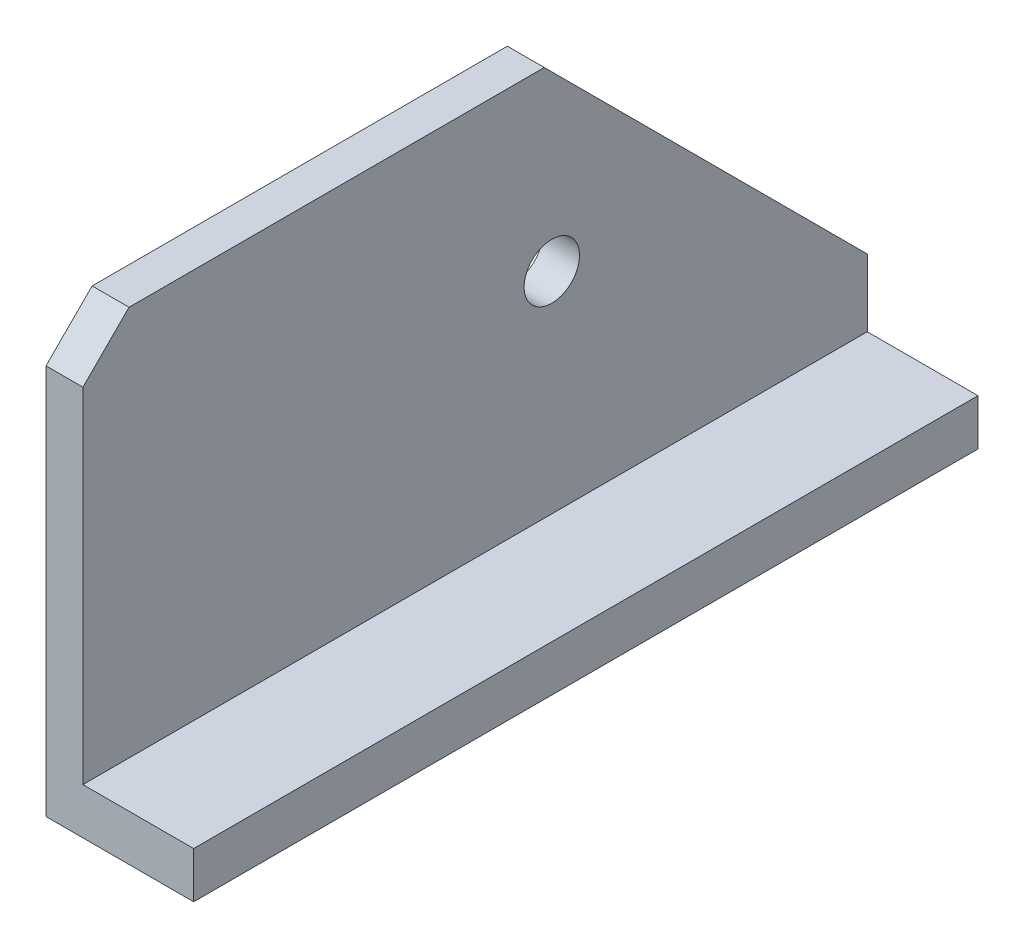
SolidWorks part; units mm, degrees
ref_plane "Спереди" through (0, 0, 0) normal (0, 0, 1) x (1, 0, 0)
ref_plane "Сверху" through (0, 0, 0) normal (0, 1, 0) x (1, 0, 0)
ref_plane "Справа" through (0, 0, 0) normal (1, 0, 0) x (0, 0, -1)
sketch "Эскиз1" plane through (0, 0, 0) normal (0, 0, 1) x (1, 0, 0)
  line L1 (0, 0) -> (12, 0)
  line L3 (-4, -5) -> (12, -5)
  line L4 (12, 0) -> (12, -5)
  line L6 (0, 0) -> (0, 42.3)
  line L7 (0, 42.3) -> (-4, 42.3)
  line L8 (-4, -5) -> (-4, 42.3)
extrude "Вытянуть1" add sketch "Эскиз1" along normal blind 85
sketch "Эскиз2" plane through (0, 0, 0) normal (1, 0, 0) x (0, 0, -1)
  circle A0 centre (-34.1865, 22.7734) radius 3
extrude "Вырез-Вытянуть1" cut sketch "Эскиз2" against normal through all
chamfer "Фаска1" distance 35 angle 45 1 edges at (-2, 42.3, 0)
chamfer "Фаска2" distance 5 angle 45 1 edges at (-2, 42.3, 85)
